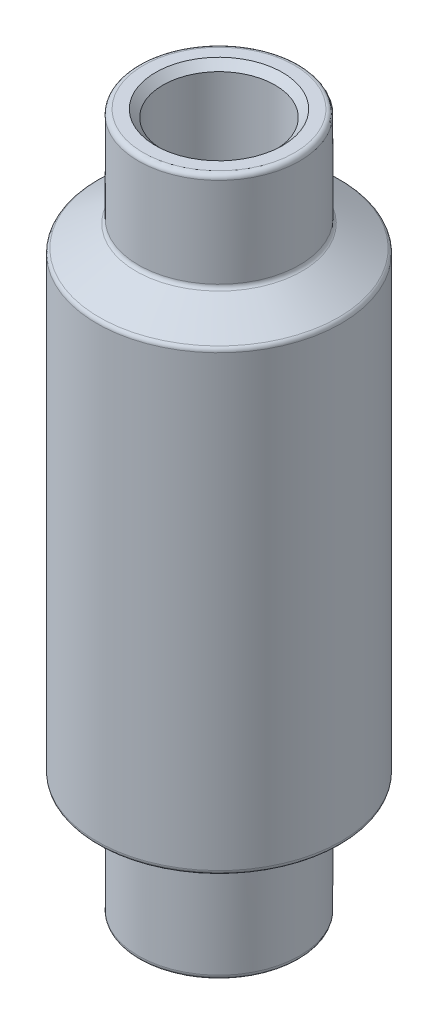
SolidWorks part; units mm, degrees
ref_plane "Front Plane" through (0, 0, 0) normal (0, 0, 1) x (1, 0, 0)
ref_plane "Top Plane" through (0, 0, 0) normal (0, 1, 0) x (1, 0, 0)
ref_plane "Right Plane" through (0, 0, 0) normal (1, 0, 0) x (0, 0, -1)
sketch "Sketch1" plane through (0, 0, 0) normal (0, 0, 1) x (1, 0, 0)
  line L0 (0, 71.5) -> (0, -71.5)
  line L1 (0, 71.5) -> (0, -71.5)
  line L2 (25, 46.5) -> (25, -46.5)
  line L3 (16.5, 51.5) -> (25, 46.5)
  line L6 (-97.8127, 0) -> (107.8505, 0) construction
  line L7 (16.5, 51.5) -> (16.5, 71.5)
  line L8 (16.5, 71.5) -> (0, 71.5)
  line L11 (16.5, -71.5) -> (0, -71.5)
  line L12 (16.5, -51.5) -> (16.5, -71.5)
  line L13 (16.5, -51.5) -> (25, -46.5)
  dimension "D3" = 16.5
  dimension "D4" = 93
  dimension "D5" = 5
revolve "Revolve2" add sketch "Sketch1" angle 360 about L0
ref_plane "Plane1" through (0, 71.5, 0) normal (0, 1, 0) x (1, 0, 0)
sketch "Sketch2" plane through (0, 71.5, 0) normal (0, 1, 0) x (1, 0, 0)
  circle A0 centre (0, 0) radius 11.5
extrude "Cut-Extrude1" cut sketch "Sketch2" against normal blind 34
mirror "Mirror1" about plane through (0, 0, 0) normal (0, 1, 0) of "Cut-Extrude1"
fillet "Fillet1" radius 1 1 edges at (-25, 46.5, 0)
fillet "Fillet2" radius 1 1 edges at (-16.5, 51.5, 0)
fillet "Fillet3" radius 1 2 edges at (-16.5, -51.5, 0) (-25, -46.5, 0)
fillet "Fillet5" radius 1 2 edges at (-16.5, -71.5, 0) (-16.5, 71.5, 0)
chamfer "Chamfer1" distance 1.5 angle 45 2 edges at (-11.5, -71.5, 0) (-11.5, 71.5, 0)
ref_plane "Plane2" through (0, 71.5, 0) normal (0, 1, 0) x (1, 0, 0)
sketch "Sketch3" plane through (0, 71.5, 0) normal (0, 1, 0) x (1, 0, 0)
  line L1 (-15.3704, 6) -> (-15.3704, -6)
  line L2 (-18.6644, 0) -> (-15.3704, 0) construction
  line L3 (15.3704, 6) -> (15.3704, -6)
  circle A1 centre (0, 0) radius 16.5 construction
  arc A2 (-15.3704, 6) -> (-15.3704, -6) centre (0, 0) ccw
  arc A3 (15.3704, -6) -> (15.3704, 6) centre (0, 0) ccw
